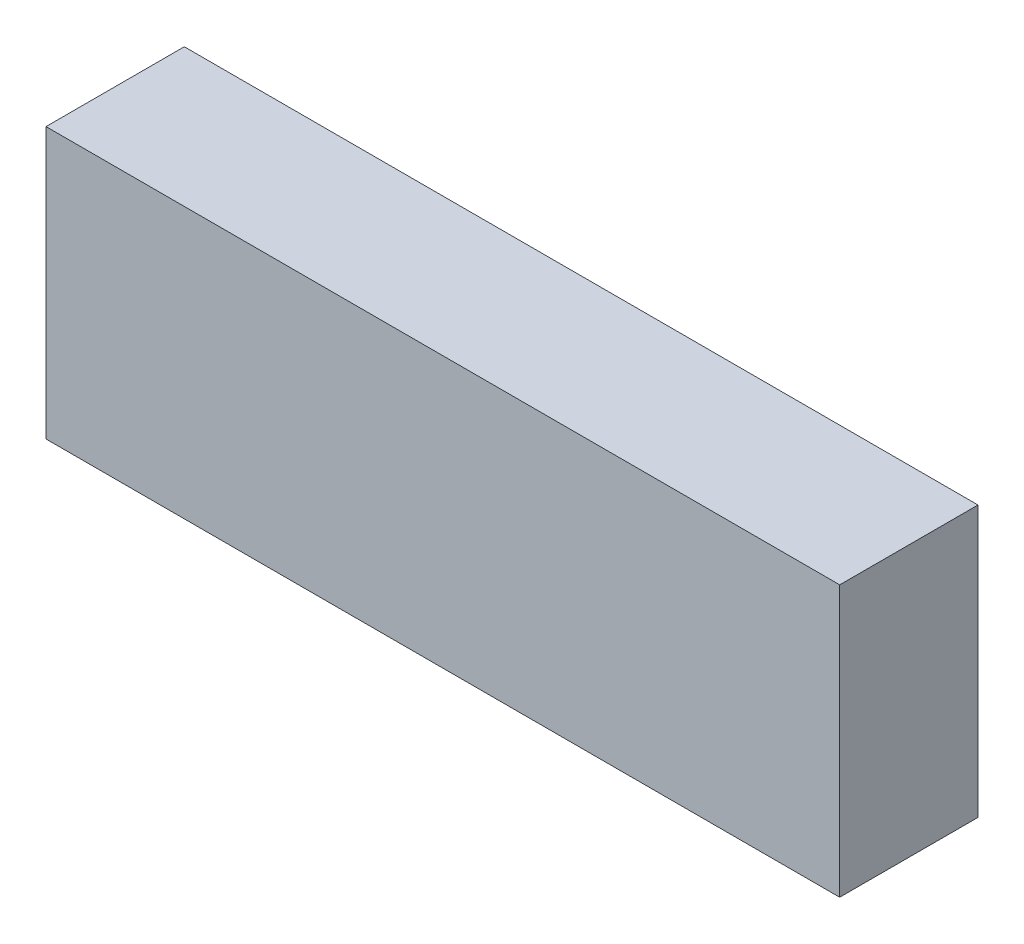
SolidWorks part; units mm, degrees
ref_plane "前基準面" through (0, 0, 0) normal (0, 0, 1) x (1, 0, 0)
ref_plane "上基準面" through (0, 0, 0) normal (0, 1, 0) x (1, 0, 0)
ref_plane "右基準面" through (0, 0, 0) normal (1, 0, 0) x (0, 0, -1)
sketch "草圖1" plane through (0, 0, 0) normal (0, 0, 1) x (1, 0, 0)
  line L1 (-66, 22.5) -> (66, 22.5)
  line L2 (-66, 22.5) -> (-66, -22.5)
  line L3 (-66, -22.5) -> (66, -22.5)
  line L4 (66, 22.5) -> (66, -22.5)
  line L5 (-66, 22.5) -> (66, -22.5) construction
  line L6 (-66, -22.5) -> (66, 22.5) construction
  point P0 (0, 0)
  dimension "D1" = 132
  dimension "D2" = 45
extrude "伸長1" add sketch "草圖1" along normal blind 23
